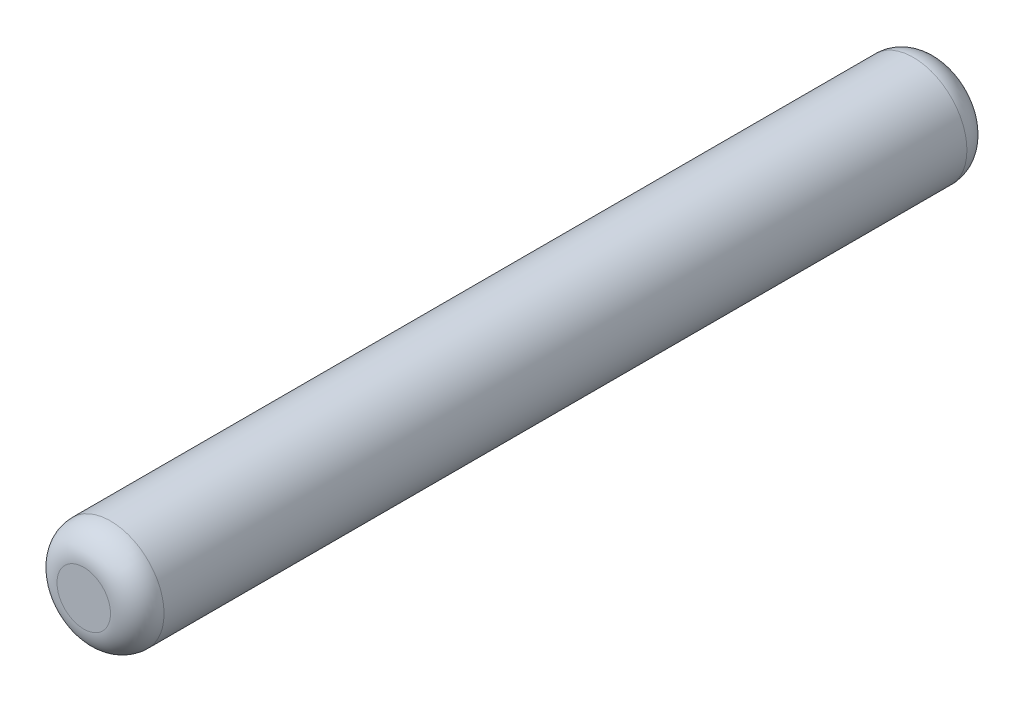
SolidWorks part; units mm, degrees
ref_plane "Front Plane" through (0, 0, 0) normal (0, 0, 1) x (1, 0, 0)
ref_plane "Top Plane" through (0, 0, 0) normal (0, 1, 0) x (1, 0, 0)
ref_plane "Right Plane" through (0, 0, 0) normal (1, 0, 0) x (0, 0, -1)
sketch "Sketch1" plane through (0, 0, 0) normal (0, 0, 1) x (1, 0, 0)
  circle A0 centre (0, 0) radius 50
  dimension "D1" = 100
extrude "Boss-Extrude1" add sketch "Sketch1" along normal mid plane 800
fillet "Fillet1" radius 25 2 edges at (50, 0, -400) (50, 0, 400)
